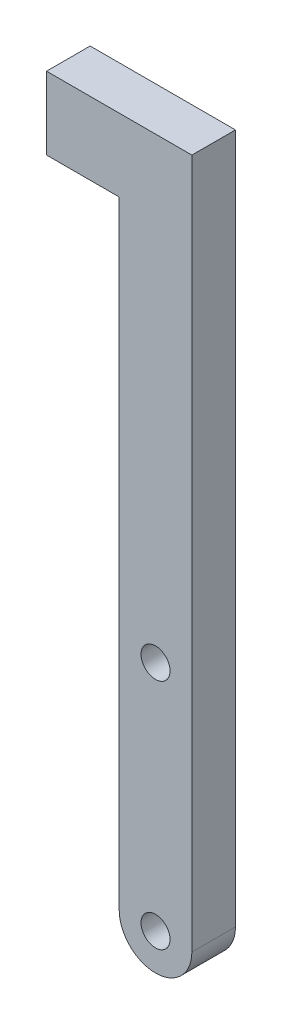
SolidWorks part; units mm, degrees
ref_plane "Plan de face" through (0, 0, 0) normal (0, 0, 1) x (1, 0, 0)
ref_plane "Plan de dessus" through (0, 0, 0) normal (0, 1, 0) x (1, 0, 0)
ref_plane "Plan de droite" through (0, 0, 0) normal (1, 0, 0) x (0, 0, -1)
sketch "Esquisse1" plane through (0, 0, 0) normal (0, 0, 1) x (1, 0, 0)
  line L0 (0, 0) -> (10, 0)
  line L1 (10, 0) -> (10, -47.5)
  line L2 (0, 0) -> (0, -5)
  line L3 (0, -5) -> (5, -5)
  line L4 (5, -5) -> (5, -47.5)
  arc A0 (5, -47.5) -> (10, -47.5) centre (7.5, -47.5) ccw
  point P8 (7.5, -50)
  point P9 (2.5, -5)
  dimension "D1" = 45
  dimension "D2" = 10
  dimension "D3" = 5
  dimension "D4" = 5
extrude "Boss.-Extru.1" add sketch "Esquisse1" along normal blind 3
sketch "Esquisse3" plane through (0, 0, 0) normal (0, 0, -1) x (-1, 0, 0)
  line L0 (-10, -47.5) -> (-5, -47.5) construction
  arc A0 (-10, -47.5) -> (-5, -47.5) centre (-7.5, -47.5) ccw construction
  circle A1 centre (-7.5, -47.5) radius 1
  dimension "D1" = 2
extrude "Enlèv. mat.-Extru.1" cut sketch "Esquisse3" against normal blind 4
sketch "Esquisse4" plane through (0, 0, 3) normal (0, 0, 1) x (1, 0, 0)
  line L0 (7.5, -46.5) -> (7.5, -31.5) construction
  circle A0 centre (7.5, -47.5) radius 1 construction
  circle A1 centre (7.5, -31.5) radius 1
  dimension "D2" = 2
  dimension "D1" = 15
extrude "Enlèv. mat.-Extru.2" cut sketch "Esquisse4" against normal blind 10
